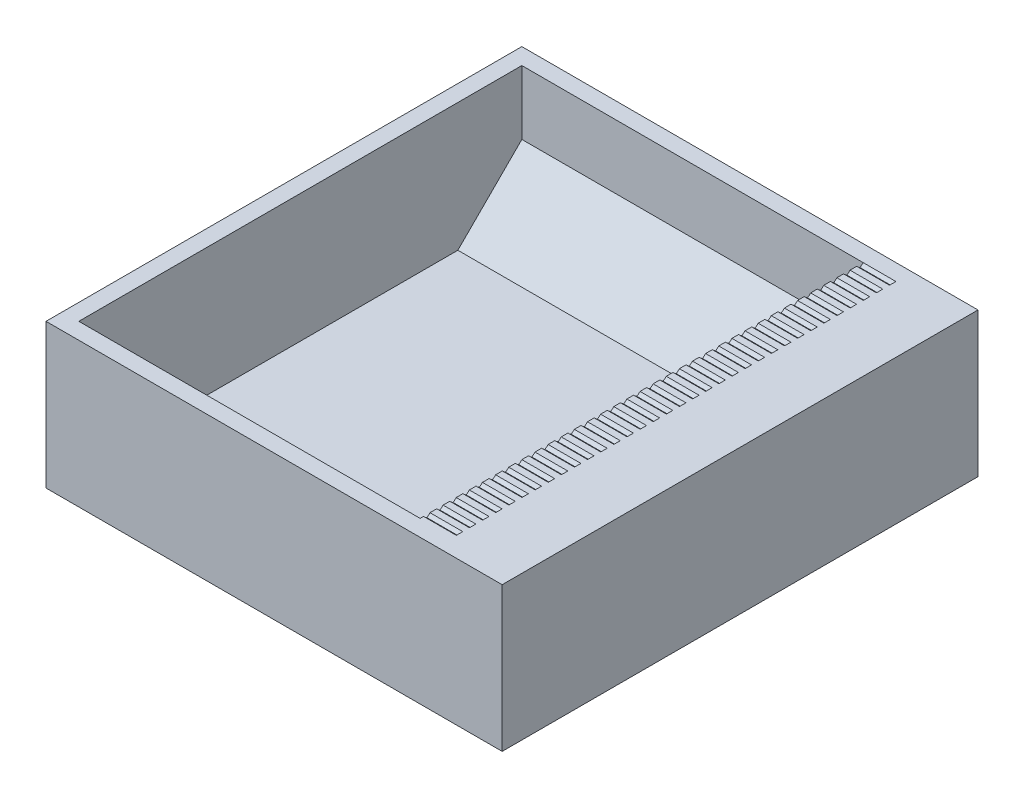
SolidWorks part; units mm, degrees
ref_plane "정면" through (0, 0, 0) normal (0, 0, 1) x (1, 0, 0)
ref_plane "윗면" through (0, 0, 0) normal (0, 1, 0) x (1, 0, 0)
ref_plane "우측면" through (0, 0, 0) normal (1, 0, 0) x (0, 0, -1)
sketch "스케치1" plane through (0, 0, 0) normal (1, 0, 0) x (0, 0, -1)
  line L0 (0, 0) -> (-145, 0)
  line L1 (-145, 0) -> (-145, 44)
  line L2 (-145, 44) -> (0, 44)
  line L3 (0, 44) -> (0, 0)
  dimension "D1" = 44
  dimension "D2" = 145
extrude "보스-돌출1" add sketch "스케치1" along normal blind 139 contours L2 L3 L0 L1
shell "쉘1" thickness 5
sketch "스케치3" plane through (5, 0, 0) normal (1, 0, 0) x (0, 0, -1)
  line L0 (-5, 24.5) -> (-24.5, 5)
  line L1 (-5, 44) -> (-5, 5) construction
  line L2 (-5, 5) -> (-140, 5) construction
  line L3 (-24.5, 5) -> (-5, 5)
  line L4 (-5, 5) -> (-5, 24.5)
  line L5 (-5, 24.5) -> (-21.4438, 24.5) construction
  dimension "D1" = 45
extrude "보스-돌출2" add sketch "스케치3" along normal up to next
sketch "스케치4" plane through (109, 0, 0) normal (-1, 0, 0) x (0, 0, 1)
  line L0 (119.462, 56.1) -> (5.9787, 56.1) construction
  line L1 (4.1681, 46.2653) -> (4.1681, 55.5386) construction
  line L2 (4.1681, 46.2653) -> (7.7893, 46.2653)
  line L3 (5.9787, 56.1) -> (5.9787, 43.2) construction
  arc A0 (5.9787, 43.2) -> (4.1681, 46.2653) centre (7.6681, 46.2653) cw
  arc A2 (5.9787, 43.2) -> (7.7893, 46.2653) centre (4.2893, 46.2653) ccw
  circle A3 centre (5.9787, 56.1) radius 10 construction
  point P0 (119.462, 56.1)
  dimension "D2" = 3.5
  dimension "D3" = 20
  dimension "D1" = 12.9
extrude "컷-돌출1" cut sketch "스케치4" against normal up to surface (10 mm away)
pattern_linear "선형 패턴2" count 34 spacing 4 along (0, 0, 1) of "컷-돌출1"
